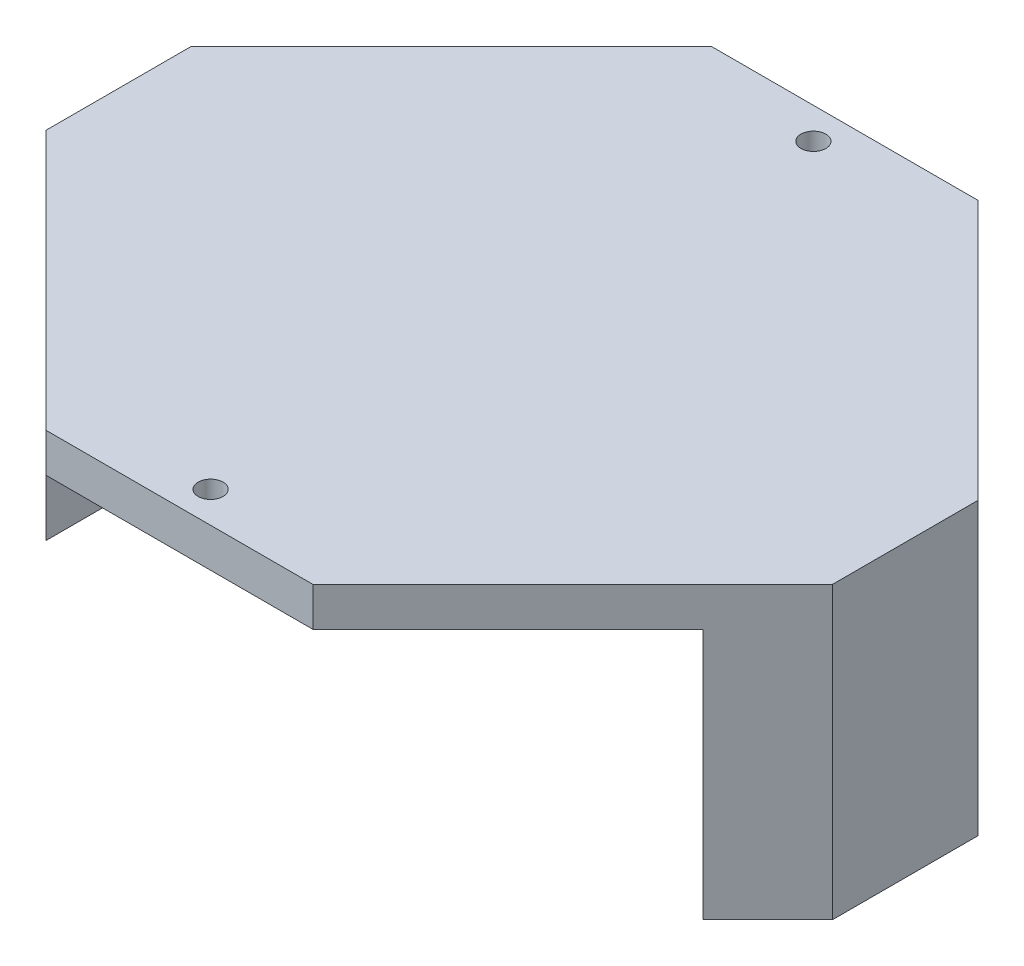
SolidWorks part; units mm, degrees
ref_plane "Front Plane" through (0, 0, 0) normal (0, 0, 1) x (1, 0, 0)
ref_plane "Top Plane" through (0, 0, 0) normal (0, 1, 0) x (1, 0, 0)
ref_plane "Right Plane" through (0, 0, 0) normal (1, 0, 0) x (0, 0, -1)
sketch "Sketch1" plane through (0, 0, 0) normal (0, 0, 1) x (1, 0, 0)
  line L1 (-48.0568, 17.7482) -> (48.0568, 17.7482)
  line L2 (-48.0568, 17.7482) -> (-48.0568, -17.7482)
  line L3 (-48.0568, -17.7482) -> (48.0568, -17.7482)
  line L4 (48.0568, 17.7482) -> (48.0568, -17.7482)
  line L5 (-48.0568, 17.7482) -> (48.0568, -17.7482) construction
  line L6 (-48.0568, -17.7482) -> (48.0568, 17.7482) construction
  line L7 (-40.132, 12.9857) -> (40.132, 12.9857)
  line L8 (-40.132, 12.9857) -> (-40.132, -17.7482)
  line L9 (-40.132, -17.7482) -> (40.132, -17.7482)
  line L10 (40.132, 12.9857) -> (40.132, -17.7482)
  line L11 (-40.132, 12.9857) -> (40.132, -17.7482) construction
  line L12 (-40.132, -17.7482) -> (40.132, 12.9857) construction
  point P0 (0, 0)
  point P6 (0, -2.3812)
  point P11 (0, 0)
  dimension "D1" = 80.264
  dimension "D2" = 4.7625
  dimension "D3" = 7.9248
  dimension "D4" = 30.734
extrude "Boss-Extrude1" add sketch "Sketch1" along normal mid plane 81.28 contours L7 L10 L3 L4 L1 L2 L8
hole_wizard "#31 (0.12) Diameter Hole2" positions "Sketch2" profile "Sketch4" hole size "#31" standard "ANSI Inch"
sketch "Sketch2" plane through (0, -17.7482, 0) normal (0, -1, 0) x (-1, 0, 0)
  line L0 (40.132, -40.64) -> (48.0568, 40.64)
  line L1 (48.0568, 40.64) -> (-48.0568, 40.64)
  line L2 (-48.0568, 40.64) -> (-40.132, -40.64)
  point P11 (44.0944, 0)
  point P13 (-44.0944, 0)
sketch "Sketch4" plane through (44.0944, -17.7482, 0) normal (1, 0, 0) x (0, 0, -1)
  line L0 (0, 0) -> (0, 13.6157)
  line L1 (0, 13.6157) -> (1.524, 12.7)
  line L2 (1.524, 12.7) -> (1.524, 0)
  line L5 (1.524, 0) -> (0, 0)
  line L10 (0, 13.6157) -> (-1.524, 12.7) construction
  line L11 (0, -6.35) -> (0, 107.95) construction
  dimension "Hole Dia." = 3.048
  dimension "Hole Depth" = 12.7
  dimension "Drill Angle" = 118
hole_wizard "#31 (0.12) Diameter Hole1" positions "Sketch5" profile "Sketch6" hole size "#31" standard "ANSI Inch"
sketch "Sketch5" plane through (0, 17.7482, 0) normal (0, 1, 0) x (1, 0, 0)
  line L0 (0, -36.83) -> (0, 36.83)
  point P1 (0, -36.83)
  point P2 (0, 36.83)
  dimension "D1" = 73.66
sketch "Sketch6" plane through (0, 17.7482, 36.83) normal (1, 0, 0) x (0, 0, 1)
  line L0 (0, 0) -> (0, 13.6157)
  line L1 (0, 13.6157) -> (1.524, 12.7)
  line L2 (1.524, 12.7) -> (1.524, 0)
  line L5 (1.524, 0) -> (0, 0)
  line L10 (0, 13.6157) -> (-1.524, 12.7) construction
  line L11 (0, -6.35) -> (0, 107.95) construction
  dimension "Hole Dia." = 3.048
  dimension "Hole Depth" = 12.7
  dimension "Drill Angle" = 118
chamfer "Chamfer1" distance 31.75 angle 45 4 edges at (-48.0568, 0, 40.64) (-48.0568, 0, -40.64) (48.0568, 0, -40.64) (48.0568, 0, 40.64)
